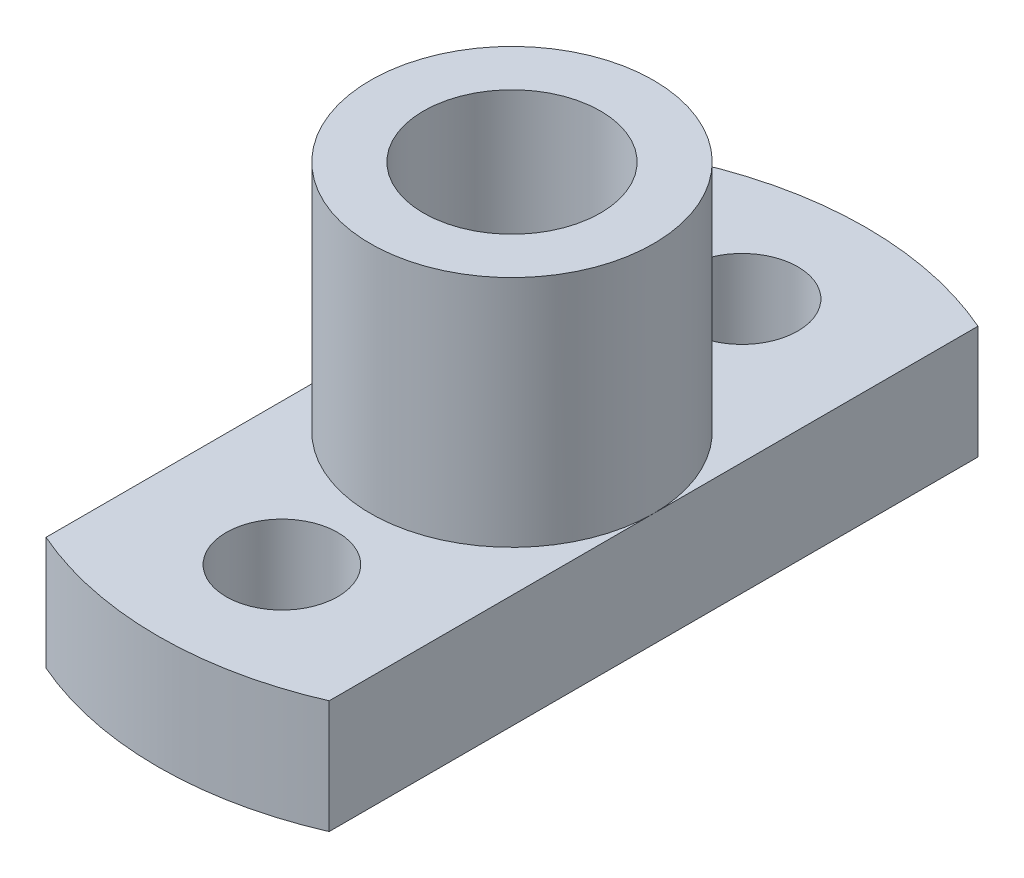
SolidWorks part; units mm, degrees
material "Laiton"
ref_plane "Plan de face" through (0, 0, 0) normal (0, 0, 1) x (1, 0, 0)
ref_plane "Plan de dessus" through (0, 0, 0) normal (0, 1, 0) x (1, 0, 0)
ref_plane "Plan de droite" through (0, 0, 0) normal (1, 0, 0) x (0, 0, -1)
sketch "Esquisse1" plane through (0, 0, 0) normal (0, 0, 1) x (1, 0, 0)
  line L0 (0, 0) -> (0, 7.6852) construction
  line L1 (2.5, 0) -> (10, 0)
  line L2 (10, 0) -> (10, 3.2)
  line L3 (10, 3.2) -> (4, 3.2)
  line L4 (4, 3.2) -> (4, 9.8)
  line L5 (4, 9.8) -> (2.5, 9.8)
  line L6 (2.5, 9.8) -> (2.5, 0)
  dimension "D1" = 5
  dimension "D2" = 8
  dimension "D3" = 9.8
  dimension "D4" = 3.2
  dimension "D5" = 20
revolve "Révolution1" add sketch "Esquisse1" angle 360 about L0
sketch "Esquisse2" plane through (0, 0, 0) normal (0, -1, 0) x (1, 0, 0)
  line L0 (0, 6.5) -> (5.6292, -3.25) construction
  line L1 (5.6292, -3.25) -> (-5.6292, -3.25) construction
  line L2 (-5.6292, -3.25) -> (0, 6.5) construction
  circle A0 centre (0, 0) radius 6.5 construction
  circle A1 centre (0, 6.5) radius 1.575
  circle A2 centre (5.6292, -3.25) radius 1.575
  circle A3 centre (-5.6292, -3.25) radius 1.575
  circle A4 centre (0, -6.5) radius 1.575
  circle A7 centre (0, 0) radius 10 construction
  dimension "D1" = 3.15
  dimension "D2" = 13
  dimension "D3" = 1.925
extrude "Enlèv. mat.-Extru.1" cut sketch "Esquisse2" against normal through all
sketch "Esquisse3" plane through (0, 0, 0) normal (0, -1, 0) x (1, 0, 0)
  line L0 (4, -10) -> (-4, 10) construction
  line L1 (4, -10) -> (-4, -10)
  line L2 (4, -10) -> (4, 10)
  line L3 (4, 10) -> (-4, 10)
  line L4 (-4, -10) -> (-4, 10)
  circle A0 centre (0, 0) radius 10 construction
  dimension "D1" = 8
extrude "Enlèv. mat.-Extru.2" cut sketch "Esquisse3" against normal through all flip side to cut
